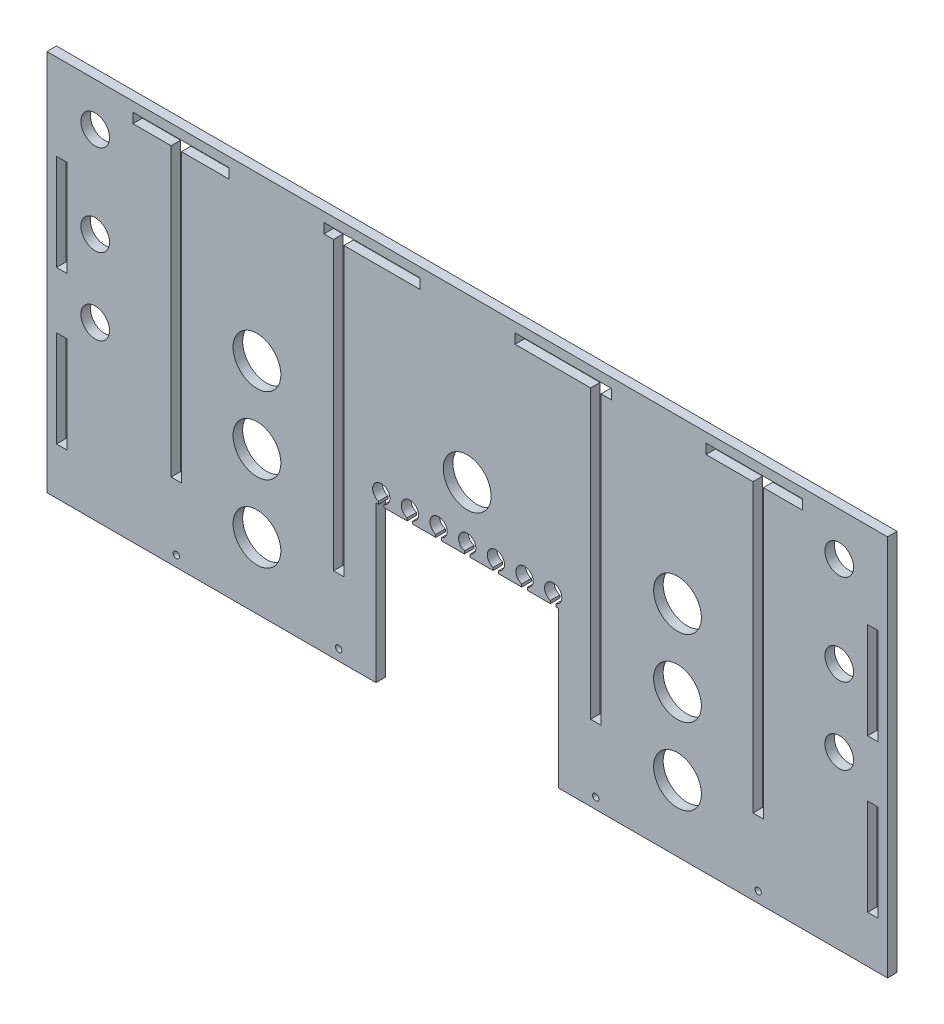
SolidWorks part; units mm, degrees
material "Acrylique (impact moyen-haut)"
ref_plane "Plan de face" through (0, 0, 0) normal (0, 0, 1) x (1, 0, 0)
ref_plane "Plan de dessus" through (0, 0, 0) normal (0, 1, 0) x (1, 0, 0)
ref_plane "Plan de droite" through (0, 0, 0) normal (1, 0, 0) x (0, 0, -1)
sketch "Esquisse1" plane through (0, 0, 0) normal (0, 0, 1) x (1, 0, 0)
  line L0 (-220, 100) -> (-0.1458, 100)
  line L1 (220, -100) -> (47.7616, -100)
  line L2 (220, -100) -> (220, 100)
  line L4 (-220, -100) -> (-220, 100)
  line L5 (220, -100) -> (-220, 100) construction
  line L6 (220, 100) -> (-220, -100) construction
  line L7 (220, 100) -> (9.8542, 100)
  line L10 (-0.1458, 100) -> (9.8542, 100)
  line L11 (-70, 89.8) -> (-70, -60.4)
  line L13 (-155, 89.8) -> (-155, -60.4)
  line L14 (-155, -60.4) -> (-149.6, -60.4)
  line L15 (-149.6, 89.8) -> (-149.6, -60.4)
  line L16 (-64.6, 89.8) -> (-64.6, -60.4)
  line L18 (-70, -60.4) -> (-64.6, -60.4)
  line L19 (0, 0) -> (0, -146.4766) construction
  line L20 (155, -60.4) -> (149.6, -60.4)
  line L21 (149.6, 89.8) -> (149.6, -60.4)
  line L23 (155, 89.8) -> (155, -60.4)
  line L25 (64.6, 89.8) -> (64.6, -60.4)
  line L26 (70, -60.4) -> (64.6, -60.4)
  line L27 (70, 89.8) -> (70, -60.4)
  line L28 (-47.7616, -100) -> (-47.7616, -18.538)
  line L29 (-47.7616, -18.538) -> (-46.4816, -18.538)
  line L30 (47.7616, -100) -> (47.7616, -18.538)
  line L31 (-47.7616, -100) -> (-220, -100)
  line L32 (-175, 95) -> (-124.6, 95)
  line L33 (-124.6, 95) -> (-124.6, 89.8)
  line L34 (-124.6, 89.8) -> (-149.6, 89.8)
  line L35 (-175, 89.8) -> (-175, 95)
  line L36 (209.6, -75.4) -> (215, -75.4) construction
  line L37 (215, -75.4) -> (215, -25) construction
  line L38 (209.6, -25) -> (209.6, -75.4) construction
  line L39 (215, -25) -> (209.6, -25) construction
  line L40 (209.6, 4.6) -> (215, 4.6) construction
  line L41 (215, 4.6) -> (215, 55) construction
  line L42 (209.6, 55) -> (209.6, 4.6) construction
  line L43 (215, 55) -> (209.6, 55) construction
  line L44 (175.4, 89.8) -> (175.4, 95) construction
  line L45 (125, 89.8) -> (175.4, 89.8) construction
  line L46 (175.4, 95) -> (125, 95) construction
  line L47 (125, 95) -> (125, 89.8) construction
  line L48 (75.4, 89.8) -> (75.4, 95) construction
  line L49 (25, 95) -> (25, 89.8) construction
  line L50 (25, 89.8) -> (75.4, 89.8) construction
  line L51 (75.4, 95) -> (25, 95) construction
  line L52 (-24.6, 95) -> (-75, 95) construction
  line L53 (-75, 89.8) -> (-24.6, 89.8) construction
  line L54 (-24.6, 89.8) -> (-24.6, 95) construction
  line L55 (-75, 95) -> (-75, 89.8) construction
  line L56 (-215, -75.4) -> (-209.6, -75.4) construction
  line L57 (-209.6, -25) -> (-215, -25) construction
  line L58 (-209.6, -75.4) -> (-209.6, -25) construction
  line L59 (-215, -25) -> (-215, -75.4) construction
  line L60 (-209.6, 4.6) -> (-209.6, 55) construction
  line L61 (-215, 4.6) -> (-209.6, 4.6) construction
  line L62 (-215, 55) -> (-215, 4.6) construction
  line L63 (-209.6, 55) -> (-215, 55) construction
  line L64 (209.6, -75.4) -> (215, -75.4)
  line L65 (215, -75.4) -> (215, -25)
  line L66 (209.6, -25) -> (209.6, -75.4)
  line L67 (215, -25) -> (209.6, -25)
  line L68 (209.6, 4.6) -> (215, 4.6)
  line L69 (215, 4.6) -> (215, 55)
  line L70 (209.6, 55) -> (209.6, 4.6)
  line L71 (215, 55) -> (209.6, 55)
  line L72 (175.4, 89.8) -> (175.4, 95)
  line L73 (125, 89.8) -> (149.6, 89.8)
  line L74 (175.4, 95) -> (125, 95)
  line L75 (125, 95) -> (125, 89.8)
  line L76 (75.4, 89.8) -> (75.4, 95)
  line L77 (25, 95) -> (25, 89.8)
  line L78 (25, 89.8) -> (64.6, 89.8)
  line L79 (75.4, 95) -> (25, 95)
  line L80 (-24.6, 95) -> (-75, 95)
  line L81 (-75, 89.8) -> (-70, 89.8)
  line L82 (-24.6, 89.8) -> (-24.6, 95)
  line L83 (-75, 95) -> (-75, 89.8)
  line L84 (-215, -75.4) -> (-209.6, -75.4)
  line L85 (-209.6, -25) -> (-215, -25)
  line L86 (-209.6, -75.4) -> (-209.6, -25)
  line L87 (-215, -25) -> (-215, -75.4)
  line L88 (-209.6, 4.6) -> (-209.6, 55)
  line L89 (-215, 4.6) -> (-209.6, 4.6)
  line L90 (-215, 55) -> (-215, 4.6)
  line L91 (-209.6, 55) -> (-215, 55)
  line L92 (-155, 89.8) -> (-175, 89.8)
  line L93 (-64.6, 89.8) -> (-24.6, 89.8)
  line L94 (70, 89.8) -> (75.4, 89.8)
  line L95 (155, 89.8) -> (175.4, 89.8)
  line L96 (-1.4816, -17.1251) -> (-1.4816, -18.538)
  line L97 (1.4816, -17.1251) -> (1.4816, -18.538)
  line L98 (1.4816, -18.538) -> (13.5184, -18.538)
  line L99 (13.5184, -17.1251) -> (13.5184, -18.538)
  line L100 (16.4816, -17.1251) -> (16.4816, -18.538)
  line L101 (28.5184, -17.1251) -> (28.5184, -18.538)
  line L102 (31.4816, -17.1251) -> (31.4816, -18.538)
  line L103 (43.5184, -17.1251) -> (43.5184, -18.538)
  line L104 (46.4816, -17.1251) -> (46.4816, -18.538)
  line L105 (16.4816, -18.538) -> (28.5184, -18.538)
  line L106 (31.4816, -18.538) -> (43.5184, -18.538)
  line L107 (46.4816, -18.538) -> (47.7616, -18.538)
  line L108 (-16.4816, -17.1251) -> (-16.4816, -18.538)
  line L109 (-13.5184, -17.1251) -> (-13.5184, -18.538)
  line L110 (-31.4816, -17.1251) -> (-31.4816, -18.538)
  line L111 (-28.5184, -17.1251) -> (-28.5184, -18.538)
  line L112 (-46.4816, -17.1251) -> (-46.4816, -18.538)
  line L113 (-43.5184, -17.1251) -> (-43.5184, -18.538)
  line L114 (-43.5184, -18.538) -> (-31.4816, -18.538)
  line L115 (-28.5184, -18.538) -> (-16.4816, -18.538)
  line L116 (-13.5184, -18.538) -> (-1.4816, -18.538)
  circle A1 centre (-152.3, -94.377) radius 1.65
  circle A2 centre (-67.3, -94.377) radius 1.65
  circle A3 centre (67.3, -94.377) radius 1.65
  circle A4 centre (152.3, -94.377) radius 1.65
  circle A5 centre (-194.7308, 77.3) radius 7.5
  circle A6 centre (-194.7308, -10.2) radius 7.5
  circle A7 centre (-194.7308, 29.8) radius 7.5
  circle A8 centre (194.7308, -10.2) radius 7.5
  circle A9 centre (194.7308, 77.3) radius 7.5
  circle A10 centre (194.7308, 29.8) radius 7.5
  circle A11 centre (110.0687, 14.7) radius 12.5
  circle A12 centre (0, 14.7) radius 12.5
  circle A13 centre (-110.0687, 14.7) radius 12.5
  arc A14 (1.4816, -17.1251) -> (-1.4816, -17.1251) centre (0, -12.876) ccw
  arc A15 (16.4816, -17.1251) -> (13.5184, -17.1251) centre (15, -12.876) ccw
  arc A16 (31.4816, -17.1251) -> (28.5184, -17.1251) centre (30, -12.876) ccw
  arc A17 (46.4816, -17.1251) -> (43.5184, -17.1251) centre (45, -12.876) ccw
  arc A18 (-13.5184, -17.1251) -> (-16.4816, -17.1251) centre (-15, -12.876) ccw
  arc A19 (-28.5184, -17.1251) -> (-31.4816, -17.1251) centre (-30, -12.876) ccw
  arc A20 (-43.5184, -17.1251) -> (-46.4816, -17.1251) centre (-45, -12.876) ccw
  circle A21 centre (110.0687, -25.3) radius 12.5
  circle A22 centre (-110.0687, -25.3) radius 12.5
  circle A23 centre (110.0687, -65.3) radius 12.5
  circle A24 centre (-110.0687, -65.3) radius 12.5
  point P0 (0, 0)
  point P38 (0, -18.538)
  dimension "D8" = 3.3
  dimension "D3" = 15
  dimension "D5" = 15
  dimension "D10" = 15
  dimension "D11" = 25
  dimension "D12" = 25
  dimension "D13" = 9
  dimension "D1" = 200
  dimension "D2" = 440
  dimension "D4" = 5.4
  dimension "D6" = 65
  dimension "D7" = 2
  dimension "D9" = 2
  dimension "D14" = 4
  dimension "D15" = 4
  dimension "D16" = 3
extrude "Boss.-Extru.1" add sketch "Esquisse1" along normal blind 5
